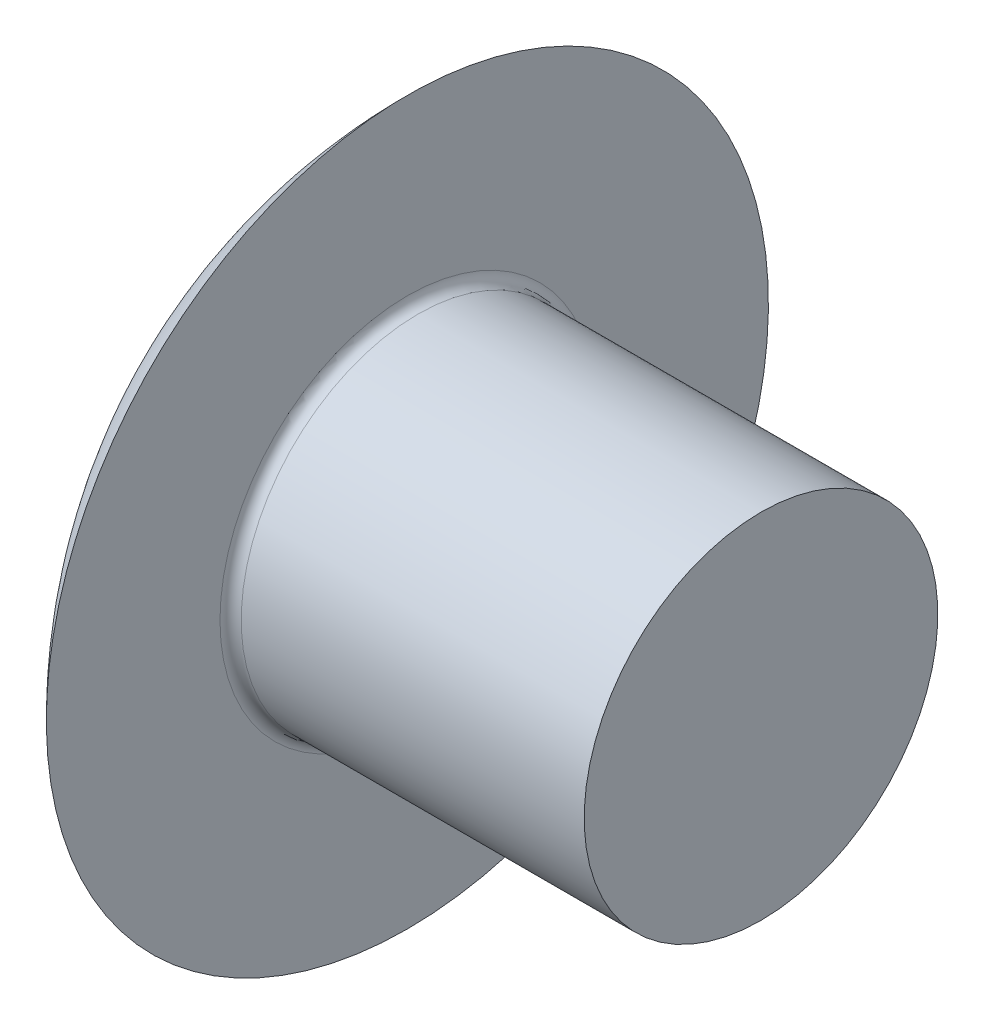
SolidWorks part; units mm, degrees
ref_plane "前视基准面" through (0, 0, 0) normal (0, 0, 1) x (1, 0, 0)
ref_plane "上视基准面" through (0, 0, 0) normal (0, 1, 0) x (1, 0, 0)
ref_plane "右视基准面" through (0, 0, 0) normal (1, 0, 0) x (0, 0, -1)
sketch "草图1" plane through (0, 0, 0) normal (0, 0, 1) x (1, 0, 0)
  line L0 (0, 0) -> (14.24, 0) construction
  line L1 (4.24, 10.21) -> (4.24, 5.3)
  line L2 (4.54, 5) -> (14.24, 5)
  line L3 (14.24, 5) -> (14.24, 0)
  line L5 (0, 0) -> (14.24, 0)
  arc A0 (4.24, 10.21) -> (0, 0) centre (14.5, -0.0361) ccw
  arc A1 (4.24, 5.3) -> (4.54, 5) centre (4.54, 5.3) ccw
  point P5 (4.24, 5)
  dimension "r_" = 0.3
  dimension "R" = 14.5
  dimension "d" = 10
  dimension "l" = 10
  dimension "dk" = 20.42
  dimension "k" = 4.24
revolve "旋转1" add sketch "草图1" angle 360 about L5
